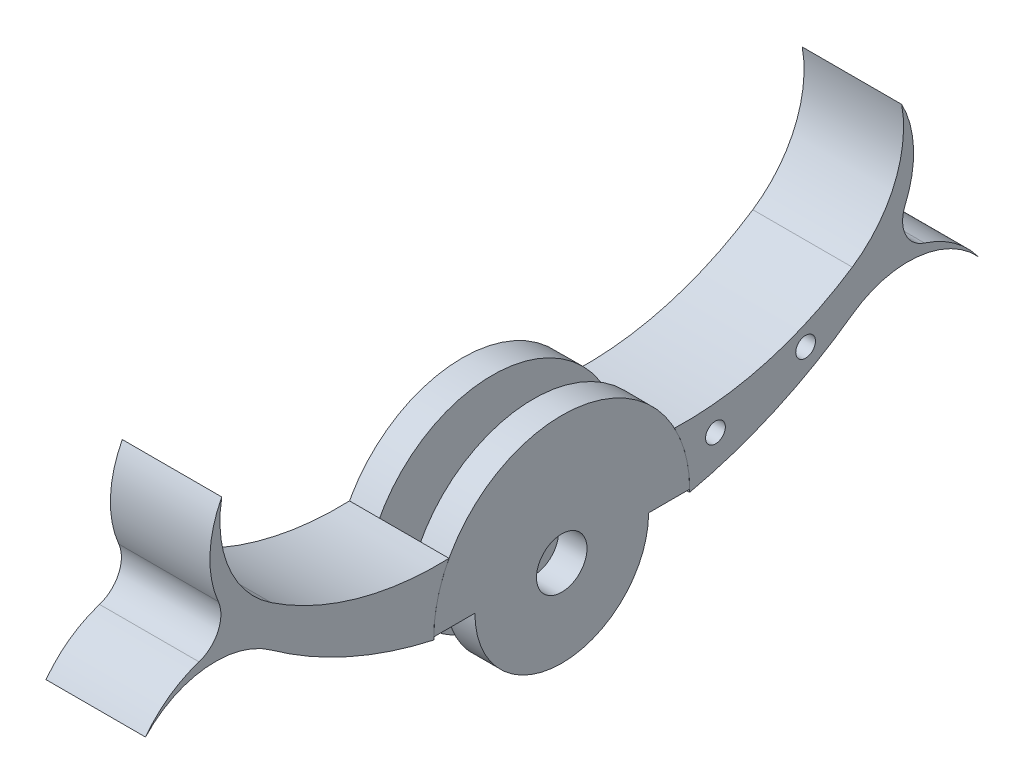
SolidWorks part; units mm, degrees
material "PVC Rigid"
ref_plane "Front Plane" through (0, 0, 0) normal (0, 0, 1) x (1, 0, 0)
ref_plane "Top Plane" through (0, 0, 0) normal (0, 1, 0) x (1, 0, 0)
ref_plane "Right Plane" through (0, 0, 0) normal (1, 0, 0) x (0, 0, -1)
sketch "Sketch1" plane through (0, 0, 0) normal (1, 0, 0) x (0, 0, -1)
  circle A0 centre (0, 0) radius 10.287
  dimension "D1" = 20.574
extrude "Boss-Extrude1" add sketch "Sketch1" along normal blind 8.001
sketch "Sketch2" plane through (8.001, 0, 0) normal (1, 0, 0) x (0, 0, -1)
  circle A0 centre (0, 0) radius 2.032
  dimension "D1" = 4.064
extrude "Cut-Extrude1" cut sketch "Sketch2" against normal blind 3.7338
sketch "Sketch3" plane through (0, 0, 0) normal (-1, 0, 0) x (0, 0, 1)
  circle A0 centre (0, 0) radius 2.032
  dimension "D1" = 4.064
extrude "Cut-Extrude2" cut sketch "Sketch3" against normal blind 3.7338
sketch "Sketch4" plane through (0, 0, 0) normal (-1, 0, 0) x (0, 0, 1)
  arc A0 (9.0665, 4.8601) -> (10.2846, -0.2199) centre (0, 0) cw
  arc A1 (10.2846, -0.2199) -> (23.3656, 5.6221) centre (2.5819, 34.5935) ccw
  circle A2 centre (0, 0) radius 10.287 construction
  arc A3 (9.0665, 4.8601) -> (23.3656, 8.9241) centre (9.8998, 29.1159) ccw
  arc A4 (23.3656, 8.9241) -> (27.3418, 18.2737) centre (18.2267, 16.6299) ccw
  arc A5 (27.3418, 18.2737) -> (27.6197, 11.1275) centre (20.0122, 14.4102) cw
  arc A6 (23.3656, 5.6221) -> (33.4757, 4.6157) centre (27.8487, -0.6271) cw
  arc A7 (33.4757, 4.6157) -> (29.1713, 7.7042) centre (26.5027, -0.5588) ccw
  arc A8 (27.6197, 11.1275) -> (29.1713, 7.7042) centre (29.9519, 10.1212) ccw
  dimension "D8" = 2.54
  dimension "D1" = 13.081
  dimension "D2" = 5.842
  dimension "D3" = 5.08
  dimension "D4" = 3.302
  dimension "D5" = 0
  dimension "D6" = 10.16
  dimension "D7" = 10.16
extrude "Boss-Extrude2" add sketch "Sketch4" against normal up to surface (8.001 mm away) separate body up to face at (8.001, 0, -2.032)
mirror "Mirror3" about plane through (0, 0, 0) normal (0, 0, 1) of bodies 104
sketch "Sketch5" plane through (8.001, 0, 0) normal (1, 0, 0) x (0, 0, -1)
  line L0 (-6.985, 0) -> (-10.287, 0)
  line L1 (6.985, 0) -> (10.287, 0)
  arc A0 (6.985, 0) -> (-6.985, 0) centre (0, 0) cw
  circle A1 centre (0, 0) radius 10.287 construction
  arc A2 (10.2846, -0.2199) -> (9.0665, 4.8601) centre (0, 0) ccw construction
  arc A3 (-10.287, 0) -> (10.287, 0) centre (0, 0) ccw
  dimension "D1" = 6.985
extrude "Cut-Extrude3" cut sketch "Sketch5" against normal up to surface (8.001 mm away) up to face at (0, 0, 2.032)
ref_plane "Plane1" through (0, 10.287, 0) normal (0, 1, 0) x (1, 0, 0)
sketch "Sketch6" plane through (0, 10.287, 0) normal (0, 1, 0) x (1, 0, 0)
  line L1 (5.715, -9.9568) -> (2.413, -9.9568)
  line L2 (5.715, -9.9568) -> (5.715, 9.9568)
  line L3 (5.715, 9.9568) -> (2.413, 9.9568)
  line L4 (2.413, -9.9568) -> (2.413, 9.9568)
  line L5 (5.715, -9.9568) -> (2.413, 9.9568) construction
  line L6 (5.715, 9.9568) -> (2.413, -9.9568) construction
  point P0 (4.064, 0)
  dimension "D1" = 4.064
  dimension "D2" = 3.302
  dimension "D3" = 19.9136
extrude "Cut-Extrude4" cut sketch "Sketch6" against normal through all
hole_wizard "1/16 (0.0625) Diameter Hole1" positions "Sketch8" profile "Sketch9" hole size "1/16" standard "ANSI Inch"
sketch "Sketch8" plane through (0, 0, 0) normal (-1, 0, 0) x (0, 0, 1)
  point P0 (-12.3622, 2.9096)
  point P2 (-19.6114, 5.2578)
  dimension "D1" = 12.7
  dimension "D2" = 7.62
sketch "Sketch9" plane through (0, 2.9096, -12.3622) normal (0, 1, 0) x (0, 0, 1)
  line L0 (0, 0) -> (0, 70.5809)
  line L1 (0, 70.5809) -> (0.7937, 70.104)
  line L2 (0.7937, 70.104) -> (0.7937, 0)
  line L5 (0.7937, 0) -> (0, 0)
  line L10 (0, 70.5809) -> (-0.7938, 70.104) construction
  line L11 (0, -6.35) -> (0, 107.95) construction
  dimension "Hole Dia." = 1.5875
  dimension "Hole Depth" = 70.104
  dimension "Drill Angle" = 118
